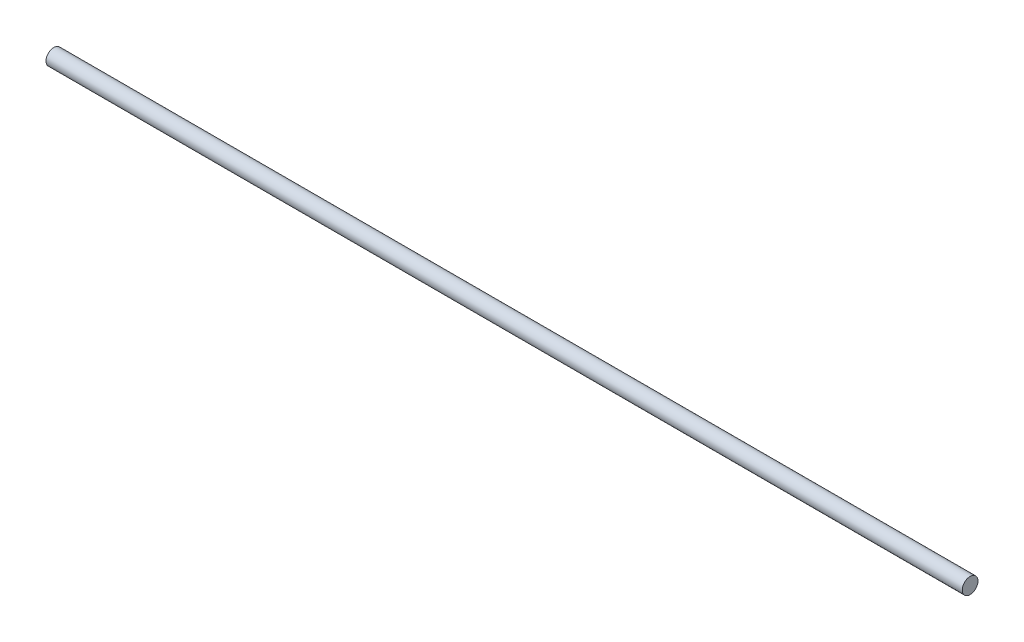
SolidWorks part; units mm, degrees
ref_plane "Front Plane" through (0, 0, 0) normal (0, 0, 1) x (1, 0, 0)
ref_plane "Top Plane" through (0, 0, 0) normal (0, 1, 0) x (1, 0, 0)
ref_plane "Right Plane" through (0, 0, 0) normal (1, 0, 0) x (0, 0, -1)
sketch "Sketch1" plane through (0, 0, 0) normal (1, 0, 0) x (0, 0, -1)
  circle A0 centre (0, 0) radius 4
  dimension "D1" = 8
extrude "Boss-Extrude1" add sketch "Sketch1" along normal blind 465
